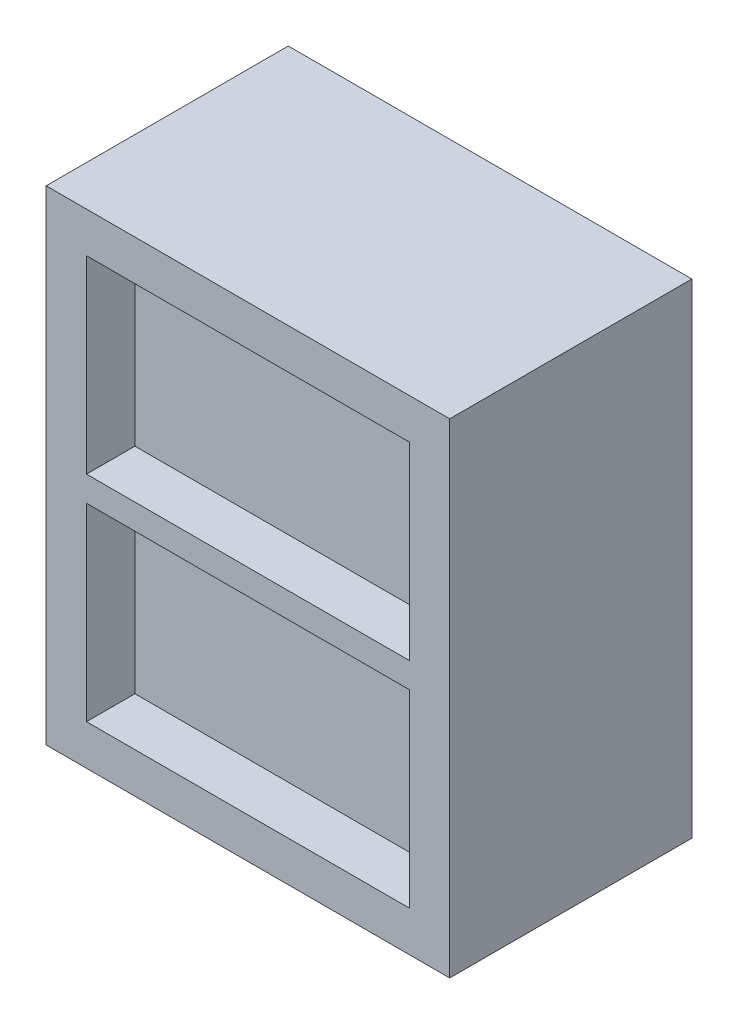
SolidWorks part; units mm, degrees
ref_plane "Alzado" through (0, 0, 0) normal (0, 0, 1) x (1, 0, 0)
ref_plane "Planta" through (0, 0, 0) normal (0, 1, 0) x (1, 0, 0)
ref_plane "Vista lateral" through (0, 0, 0) normal (1, 0, 0) x (0, 0, -1)
sketch "Croquis2" plane through (0, 0, 0) normal (0, 0, 1) x (1, 0, 0)
  line L1 (-1.25, 1.5) -> (1.25, 1.5)
  line L2 (-1.25, 1.5) -> (-1.25, -1.5)
  line L3 (-1.25, -1.5) -> (1.25, -1.5)
  line L4 (1.25, 1.5) -> (1.25, -1.5)
  line L5 (-1.25, 1.5) -> (1.25, -1.5) construction
  line L6 (-1.25, -1.5) -> (1.25, 1.5) construction
  point P0 (0, 0)
extrude "Saliente-Extruir1" add sketch "Croquis2" along normal blind 1.5
sketch "Croquis3" plane through (0, 0, 1.5) normal (0, 0, 1) x (1, 0, 0)
  line L1 (-1, 1.25) -> (1, 1.25)
  line L2 (-1, 1.25) -> (-1, -1.25)
  line L3 (-1, -1.25) -> (1, -1.25)
  line L4 (1, 1.25) -> (1, -1.25)
  line L7 (1, 0) -> (1, 1.25)
  line L8 (1, 0.625) -> (1, 0)
  line L9 (1, 0.3125) -> (1, 0)
  line L10 (1, 0.3125) -> (1, 0)
  line L11 (1, 0.1562) -> (1, 0)
  line L12 (1, 0.0781) -> (-1, 0.0781)
  line L13 (1, -0.0781) -> (-1, -0.0781)
  point P0 (0, 0)
extrude "Cortar-Extruir1" cut sketch "Croquis3" against normal blind 0.3 contours L12 L10 L8 L7 L4 L1 L2 | L4 L13 L2 L3
